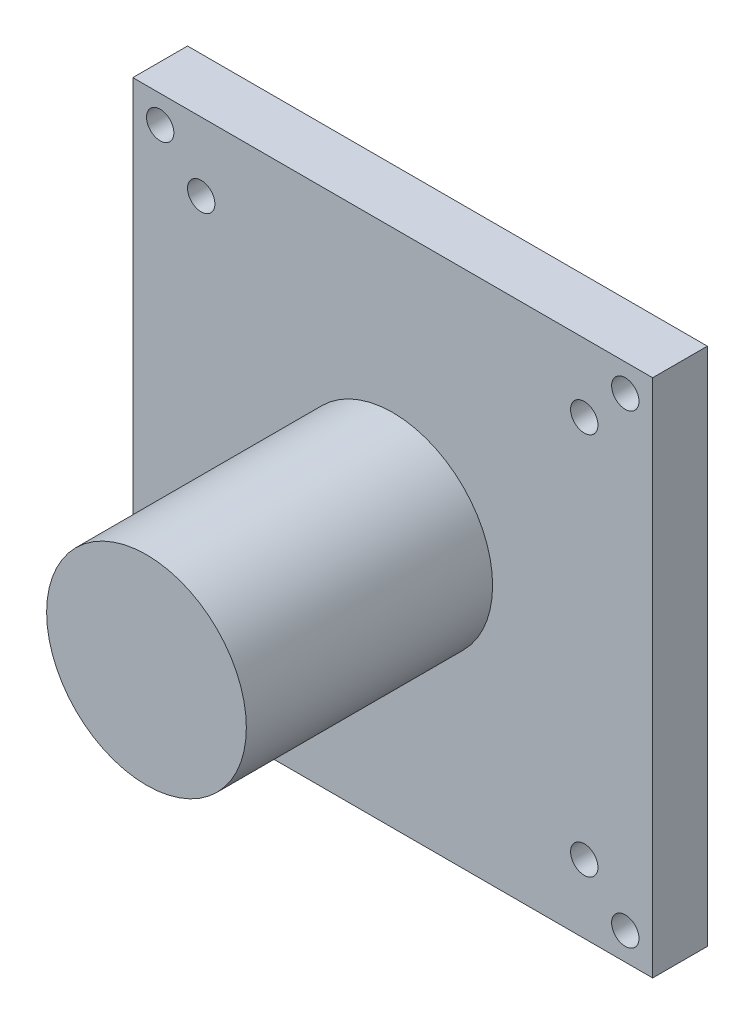
SolidWorks part; units mm, degrees
ref_plane "Front Plane" through (0, 0, 0) normal (0, 0, 1) x (1, 0, 0)
ref_plane "Top Plane" through (0, 0, 0) normal (0, 1, 0) x (1, 0, 0)
ref_plane "Right Plane" through (0, 0, 0) normal (1, 0, 0) x (0, 0, -1)
sketch "Sketch1" plane through (0, 0, 0) normal (0, 0, 1) x (1, 0, 0)
  line L0 (0, 0) -> (14, 0) construction
  line L1 (-19, -19) -> (19, -19)
  line L2 (-19, -19) -> (-19, 19)
  line L3 (-19, 19) -> (19, 19)
  line L4 (19, -19) -> (19, 19)
  line L5 (-19, -19) -> (19, 19) construction
  line L6 (-19, 19) -> (19, -19) construction
  line L7 (14, 0) -> (14, 14) construction
  line L8 (0, 0) -> (17, 0) construction
  line L9 (17, 0) -> (17, 17) construction
  line L10 (0, 0) -> (0, 6.9303) construction
  circle A1 centre (14, 14) radius 1
  circle A2 centre (17, 17) radius 1
  circle A3 centre (14, -14) radius 1
  circle A4 centre (17, -17) radius 1
  circle A5 centre (-14, -14) radius 1
  circle A6 centre (-17, -17) radius 1
  circle A7 centre (-17, 17) radius 1
  circle A8 centre (-14, 14) radius 1
  point P0 (0, 0)
extrude "Boss-Extrude1" add sketch "Sketch1" along normal blind 4
sketch "Sketch2" plane through (0, 0, 0) normal (0, 0, 1) x (1, 0, 0)
  circle A0 centre (0, 0) radius 7.3
extrude "Boss-Extrude2" add sketch "Sketch2" along normal blind 18 from surface at 4 starting at face at (0, 0, 4)
